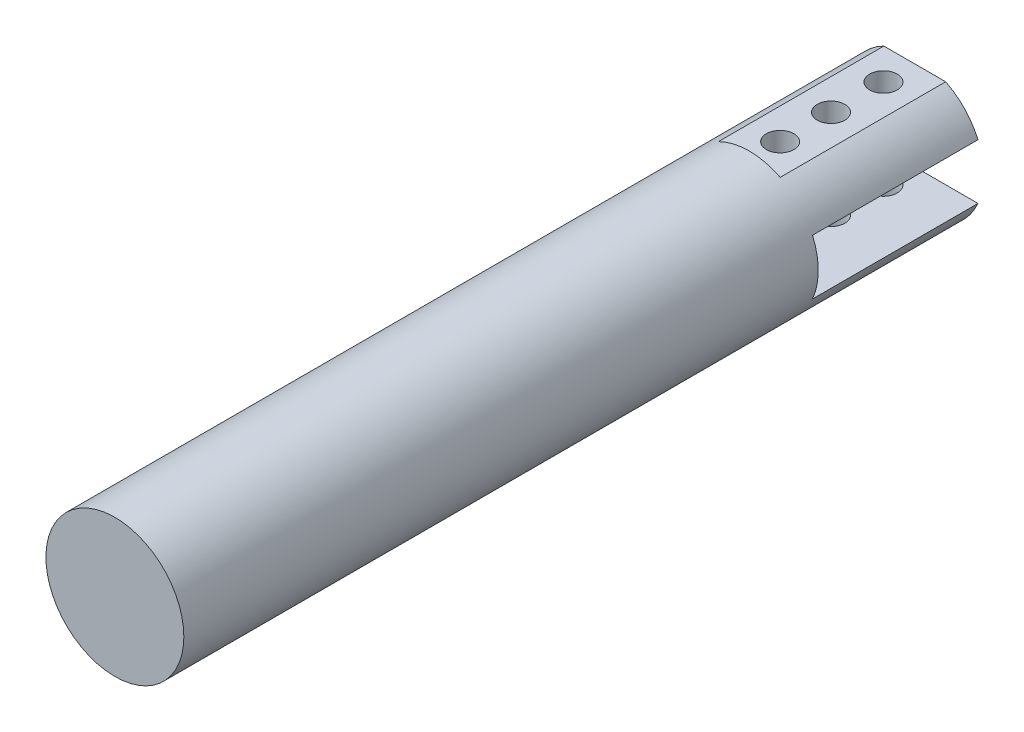
SolidWorks part; units mm, degrees
ref_plane "Спереди" through (0, 0, 0) normal (0, 0, 1) x (1, 0, 0)
ref_plane "Сверху" through (0, 0, 0) normal (0, 1, 0) x (1, 0, 0)
ref_plane "Справа" through (0, 0, 0) normal (1, 0, 0) x (0, 0, -1)
sketch "Эскиз1" plane through (0, 0, 0) normal (0, 0, 1) x (1, 0, 0)
  circle A0 centre (0, 0) radius 12.5
extrude "Вытянуть1" add sketch "Эскиз1" along normal blind 145
sketch "Эскиз2" plane through (0, 0, 0) normal (0, 0, -1) x (-1, 0, 0)
  line L1 (-35.1005, 5) -> (35.1005, 5)
  line L2 (-35.1005, 5) -> (-35.1005, -5)
  line L3 (-35.1005, -5) -> (35.1005, -5)
  line L4 (35.1005, 5) -> (35.1005, -5)
  line L5 (-35.1005, 5) -> (35.1005, -5) construction
  line L6 (-35.1005, -5) -> (35.1005, 5) construction
  point P0 (0, 0)
extrude "Вытянуть2" cut sketch "Эскиз2" against normal blind 30
sketch "Эскиз4" plane through (0, 0, 0) normal (0, 1, 0) x (1, 0, 0)
  circle A0 centre (0, -5.6806) radius 2.5
  circle A1 centre (0, -15.1858) radius 2.5
  circle A2 centre (0, -24.4088) radius 2.5
extrude "Вырез-Вытянуть1" cut sketch "Эскиз4" against normal mid plane 70
sketch "Эскиз5" plane through (0, 0, 0) normal (0, 0, -1) x (-1, 0, 0)
  line L0 (0, 0) -> (20.7443, 0) construction
  line L1 (-16.1733, -11.1738) -> (17.6231, -11.1738)
  line L2 (-16.1733, 17.6731) -> (17.6231, 17.6731)
  line L3 (-16.1733, 17.6731) -> (-16.1733, 11.1738)
  line L4 (-16.1733, 11.1738) -> (17.6231, 11.1738)
  line L5 (17.6231, 17.6731) -> (17.6231, 11.1738)
  line L6 (17.6231, -17.6731) -> (17.6231, -11.1738)
  line L7 (-16.1733, -17.6731) -> (-16.1733, -11.1738)
  line L8 (-16.1733, -17.6731) -> (17.6231, -17.6731)
extrude "Вытянуть4" cut sketch "Эскиз5" against normal blind 30
